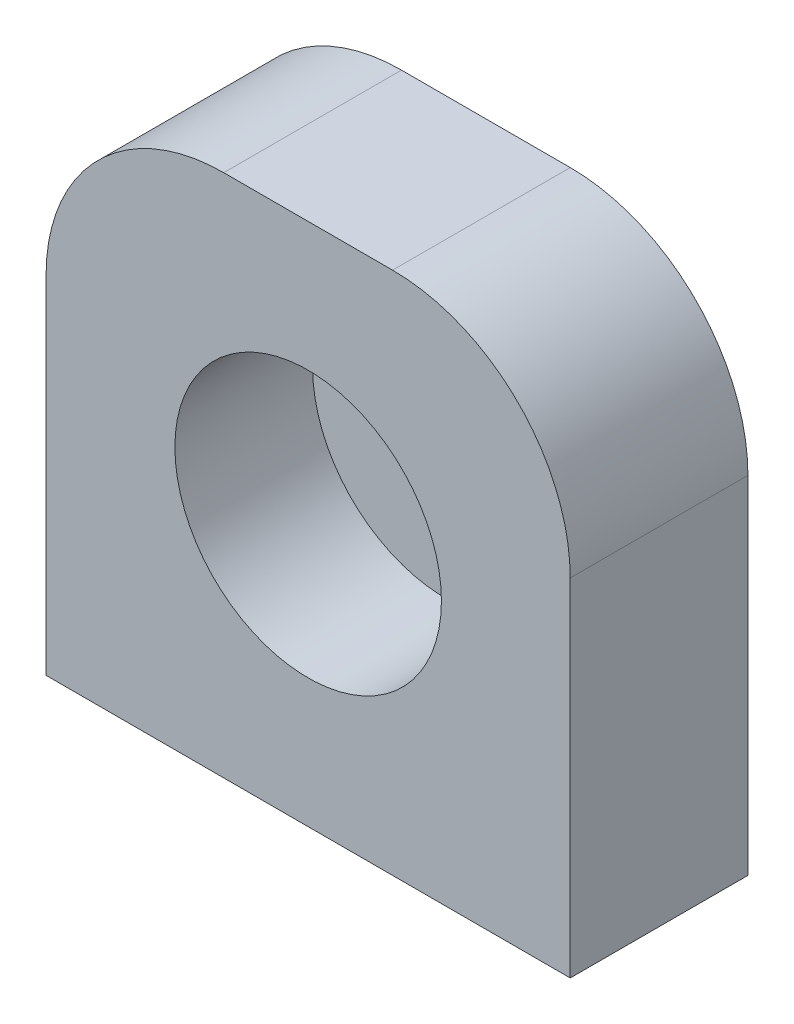
SolidWorks part; units mm, degrees
ref_plane "Front Plane" through (0, 0, 0) normal (0, 0, 1) x (1, 0, 0)
ref_plane "Top Plane" through (0, 0, 0) normal (0, 1, 0) x (1, 0, 0)
ref_plane "Right Plane" through (0, 0, 0) normal (1, 0, 0) x (0, 0, -1)
sketch "Sketch1" plane through (0, 0, 0) normal (0, 0, 1) x (1, 0, 0)
  line L1 (0, 0) -> (11.8, 0)
  line L2 (0, 0) -> (0, 11.8)
  line L3 (0, 11.8) -> (11.8, 11.8)
  line L4 (11.8, 0) -> (11.8, 11.8)
  dimension "D1" = 11.8
  dimension "D2" = 11.8
extrude "Boss-Extrude1" add sketch "Sketch1" along normal blind 4
sketch "Sketch2" plane through (0, 0, 4) normal (0, 0, 1) x (1, 0, 0)
  line L0 (5.9, 11.8) -> (5.9, 0) construction
  line L1 (11.8, 11.8) -> (0, 11.8) construction
  line L2 (0, 0) -> (11.8, 0) construction
  line L3 (11.8, 5.9) -> (0, 5.9) construction
  line L4 (11.8, 0) -> (11.8, 11.8) construction
  line L5 (0, 11.8) -> (0, 0) construction
  circle A0 centre (5.9, 5.9) radius 3
  point P14 (0, 0)
  point P15 (0, 0)
  dimension "D1" = 6
extrude "Cut-Extrude1" cut sketch "Sketch2" against normal blind 3.1
fillet "Fillet1" radius 4 2 edges at (11.8, 11.8, 2) (0, 11.8, 2)
